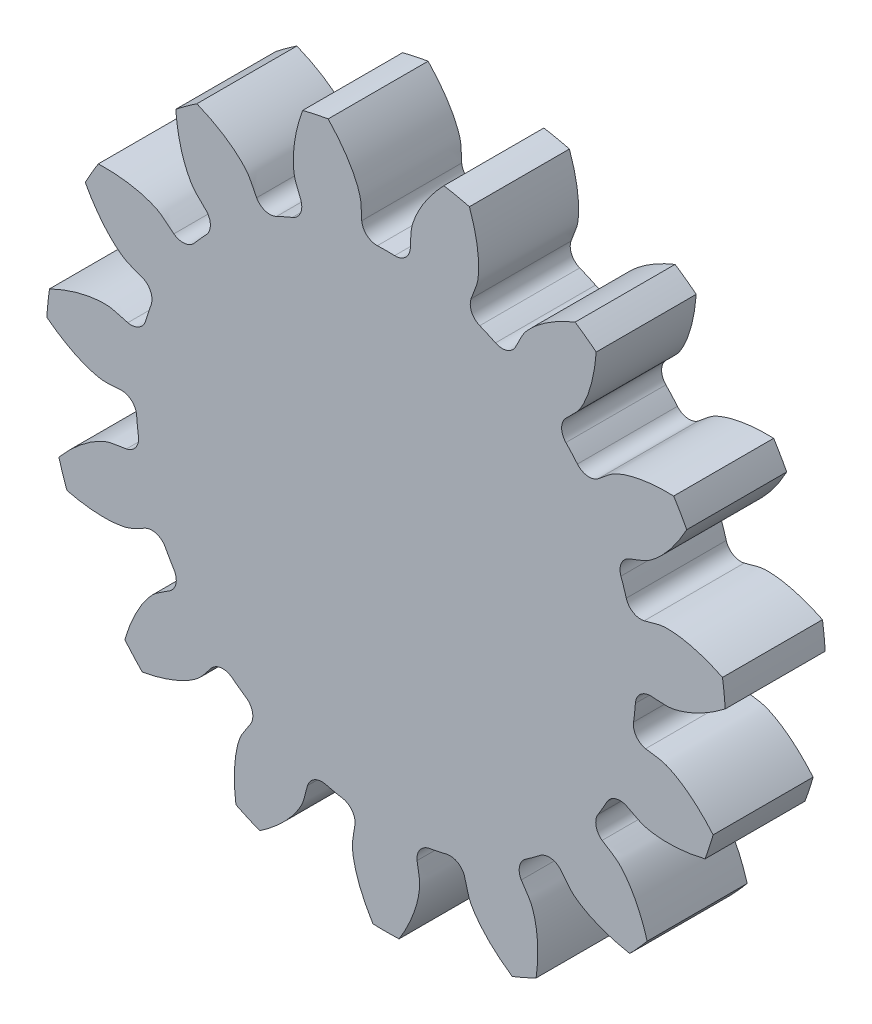
SolidWorks part; units mm, degrees
ref_plane "前视基准面" through (0, 0, 0) normal (0, 0, 1) x (1, 0, 0)
ref_plane "上视基准面" through (0, 0, 0) normal (0, 1, 0) x (1, 0, 0)
ref_plane "右视基准面" through (0, 0, 0) normal (1, 0, 0) x (0, 0, -1)
other "Configuration Table"
ref_axis "Axis1" through (0, 0, -88.99) along (0, 0, 1)
sketch "草图1" plane through (0, 0, 0) normal (0, 0, 1) x (1, 0, 0)
  circle A0 centre (0, 0) radius 17
extrude "LaShenA" add sketch "草图1" along normal blind 5
sketch "SketchA" plane through (0, 0, 5) normal (0, 0, 1) x (1, 0, 0)
  line L0 (0, 0) -> (0, 17) construction
  arc A0 (0.4317, 12.4925) -> (-0.4317, 12.4925) centre (0, 0) ccw
  arc A1 (3.8725, 17.6478) -> (-3.8725, 17.6478) centre (0, 0) ccw
  arc A2 (-0.4317, 12.4925) -> (-1.2146, 13.181) centre (-0.4579, 13.2521) cw
  arc A3 (1.2146, 13.181) -> (0.4317, 12.4925) centre (0.4579, 13.2521) cw
  circle A4 centre (0, 0) radius 14.0954 construction
  circle A5 centre (0, 0) radius 17 construction
  circle A6 centre (0, 0) radius 12.5 construction
  circle A7 centre (0, 0) radius 15 construction
  spline S0 degree 3 poles (1.2146, 13.181) (1.2415, 13.4676) (1.2219, 13.8074) (1.2883, 14.163) (1.3141, 14.2612) (1.3367, 14.3388) (1.3655, 14.4275) (1.4011, 14.527) (1.4441, 14.637) (1.4953, 14.7571) (1.5552, 14.887) (1.6244, 15.0261) (1.7037, 15.1741) (1.7934, 15.3305) (1.8943, 15.4947) (2.0068, 15.6663) (2.1315, 15.8446) (2.2689, 16.0292) (2.4194, 16.2193) (2.5835, 16.4144) (2.7615, 16.6138) (2.954, 16.8169) (3.1612, 17.0229) (3.4637, 17.3063) (3.7048, 17.5124) (3.8725, 17.6478) knots 0.123008 0.123008 0.123008 0.123008 0.262739 0.288009 0.299133 0.312281 0.327451 0.344644 0.36386 0.385098 0.408359 0.433643 0.46095 0.490279 0.521631 0.555005 0.590403 0.627823 0.667265 0.708731 0.752219 0.79773 0.845263 0.894819 1 1 1 1
  spline S1 degree 3 poles (-1.2146, 13.181) (-1.2415, 13.4676) (-1.2219, 13.8074) (-1.2883, 14.163) (-1.3141, 14.2612) (-1.3367, 14.3388) (-1.3655, 14.4275) (-1.4011, 14.527) (-1.4441, 14.637) (-1.4953, 14.7571) (-1.5552, 14.887) (-1.6244, 15.0261) (-1.7037, 15.1741) (-1.7934, 15.3305) (-1.8943, 15.4947) (-2.0068, 15.6663) (-2.1315, 15.8446) (-2.2689, 16.0292) (-2.4194, 16.2193) (-2.5835, 16.4144) (-2.7615, 16.6138) (-2.954, 16.8169) (-3.1612, 17.0229) (-3.4637, 17.3063) (-3.7048, 17.5124) (-3.8725, 17.6478) knots 0.123008 0.123008 0.123008 0.123008 0.262739 0.288009 0.299133 0.312281 0.327451 0.344644 0.36386 0.385098 0.408359 0.433643 0.46095 0.490279 0.521631 0.555005 0.590403 0.627823 0.667265 0.708731 0.752219 0.79773 0.845263 0.894819 1 1 1 1
  dimension "D1" = 0.76
  dimension "Db" = 28.1908
  dimension "Da" = 34
  dimension "Df" = 25
  dimension "Dn" = 30
extrude "Cut-ExtrudeA" cut sketch "SketchA" against normal blind 30
pattern_circular "www.KYTool.cn" count 15 over 360 about axis through (0, 0, -88.99) along (0, 0, 1) of "Cut-ExtrudeA"
